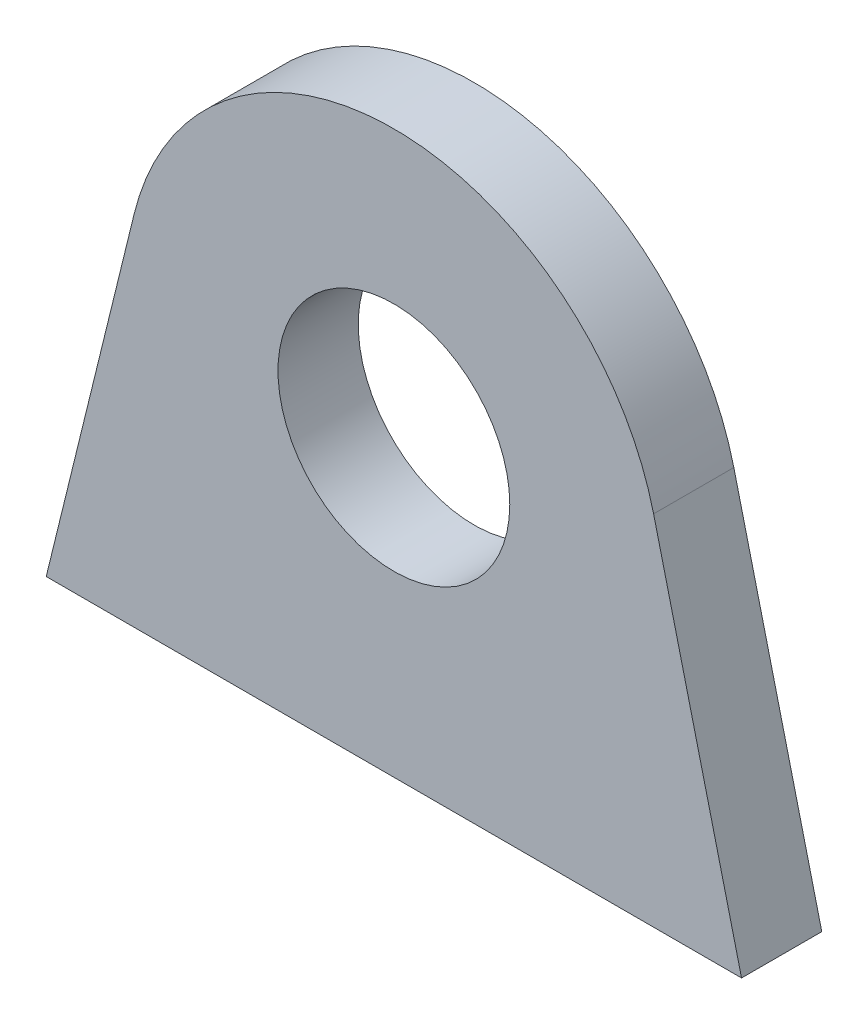
SolidWorks part; units mm, degrees
ref_plane "Front Plane" through (0, 0, 0) normal (0, 0, 1) x (1, 0, 0)
ref_plane "Top Plane" through (0, 0, 0) normal (0, 1, 0) x (1, 0, 0)
ref_plane "Right Plane" through (0, 0, 0) normal (1, 0, 0) x (0, 0, -1)
sketch "Sketch1" plane through (0, 0, 0) normal (0, 0, 1) x (1, 0, 0)
  line L0 (0, 58.6646) -> (0, -33) construction
  line L1 (-39, -33) -> (39, -33)
  line L2 (-39, -33) -> (-29.1336, 7.1579)
  line L3 (39, -33) -> (29.1336, 7.1579)
  circle A0 centre (0, 0) radius 13
  arc A1 (29.1336, 7.1579) -> (-29.1336, 7.1579) centre (0, 0) ccw
  dimension "D2" = 60
  dimension "D3" = 26
  dimension "D1" = 78
  dimension "D4" = 39
  dimension "D5" = 33
extrude "Boss-Extrude1" add sketch "Sketch1" along normal blind 9
